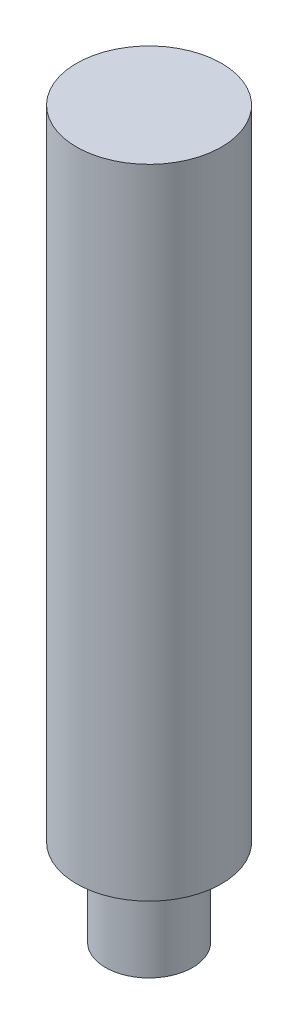
SolidWorks part; units mm, degrees
material "Cast Alloy Steel"
ref_plane "Front Plane" through (0, 0, 0) normal (0, 0, 1) x (1, 0, 0)
ref_plane "Top Plane" through (0, 0, 0) normal (0, 1, 0) x (1, 0, 0)
ref_plane "Right Plane" through (0, 0, 0) normal (1, 0, 0) x (0, 0, -1)
sketch "Sketch1" plane through (0, 0, 0) normal (1, 0, 0) x (0, 0, -1)
  line L0 (0, 0) -> (0, 25)
  line L1 (0, 25) -> (2.5, 25)
  line L2 (2.5, 25) -> (2.5, 3)
  line L3 (2.5, 3) -> (1.5, 3)
  line L4 (1.5, 3) -> (1.5, 0)
  line L5 (1.5, 0) -> (0, 0)
  dimension "D1" = 1.5
  dimension "D2" = 25
  dimension "D3" = 3
  dimension "D4" = 2.5
revolve "Revolve1" add sketch "Sketch1" angle 360 about L0
